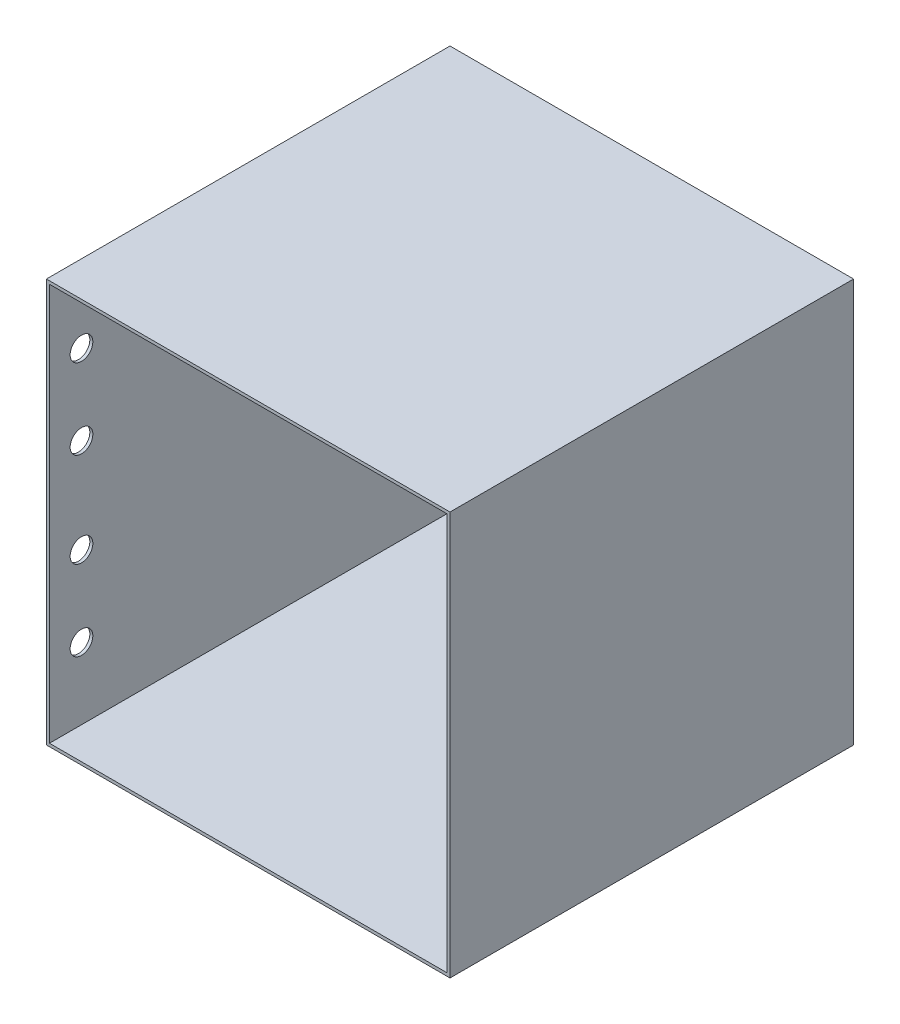
SolidWorks part; units mm, degrees
material "AISI 304"
ref_plane "Alzado" through (0, 0, 0) normal (0, 0, 1) x (1, 0, 0)
ref_plane "Planta" through (0, 0, 0) normal (0, 1, 0) x (1, 0, 0)
ref_plane "Vista lateral" through (0, 0, 0) normal (1, 0, 0) x (0, 0, -1)
sketch "Croquis1" plane through (0, 0, 0) normal (0, 0, 1) x (1, 0, 0)
  line L1 (0, 0) -> (80, 0)
  line L2 (0, 0) -> (0, 80)
  line L3 (0, 80) -> (80, 80)
  line L4 (80, 0) -> (80, 80)
  dimension "D1" = 80
  dimension "D2" = 80
extrude "Saliente-Extruir1" add sketch "Croquis1" along normal blind 80
shell "Vaciado1" thickness 0.6
hole_wizard "Taladro de margen para M41" positions "Croquis2" profile "Croquis3" hole size "M4" standard "Ansi Metric"
sketch "Croquis2" plane through (-1, -72.6309, 39.9061) normal (-1, 0, 0) x (0, 1, 0)
  point P0 (87.3934, -33.7439)
  point P3 (103.2684, -33.7439)
  point P6 (121.9934, -33.7439)
  point P9 (137.8684, -33.7439)
sketch "Croquis3" plane through (-1, 14.7625, 73.65) normal (0, 1, 0) x (0, 0, 1)
  line L0 (0, 0) -> (0, 1.599)
  line L1 (0, 1.599) -> (2.25, 1.599)
  line L2 (2.25, 1.599) -> (2.25, 0)
  line L3 (2.25, 0) -> (0, 0)
  line L4 (0, -6.35) -> (0, 107.95) construction
  dimension "Diámetro de taladro hasta el siguiente" = 4.5
  dimension "Profundidad de taladro hasta el siguiente" = 1.599
